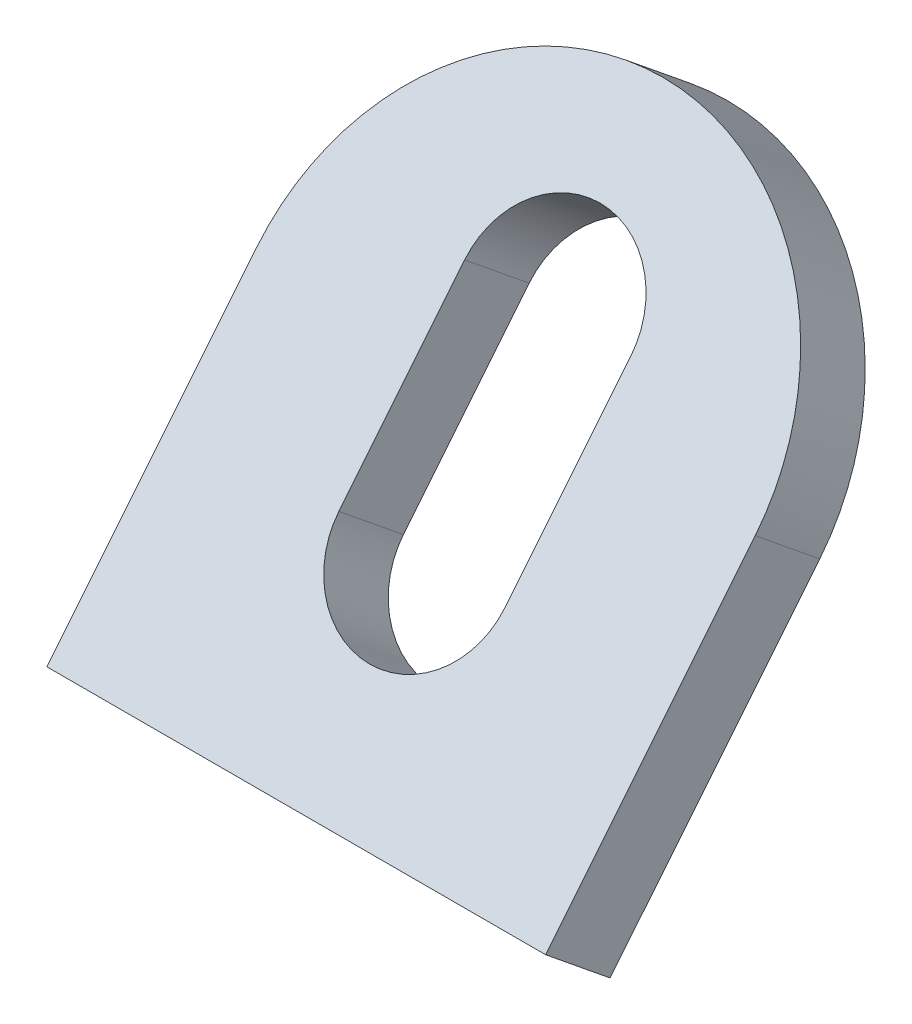
SolidWorks part; units mm, degrees
ref_plane "Front Plane" through (0, 0, 0) normal (0, 0, 1) x (1, 0, 0)
ref_plane "Top Plane" through (0, 0, 0) normal (0, 1, 0) x (1, 0, 0)
ref_plane "Right Plane" through (0, 0, 0) normal (1, 0, 0) x (0, 0, -1)
sketch "Sketch1" plane through (0, 861.7826, -474.0871) normal (0, -0.6305, -0.7762) x (1, 0, 0)
  line L0 (-319.2245, 531.8788) -> (319.2245, 531.8788) construction
  line L1 (-223.7213, 531.8788) -> (-204.6713, 531.8788)
  line L2 (-223.7213, 531.8788) -> (-223.7213, 519.1788)
  line L4 (-204.6713, 531.8788) -> (-204.6713, 519.1788)
  line L5 (-211.0213, 516.6388) -> (-211.0213, 524.2588)
  line L6 (-217.3713, 524.2588) -> (-217.3713, 516.6388)
  arc A0 (-223.7213, 519.1788) -> (-204.6713, 519.1788) centre (-214.1963, 519.1788) ccw
  arc A1 (-217.3713, 516.6388) -> (-211.0213, 516.6388) centre (-214.1963, 516.6388) ccw
  arc A2 (-211.0213, 524.2588) -> (-217.3713, 524.2588) centre (-214.1963, 524.2588) ccw
  point P16 (-214.1963, 531.8788)
  dimension "D3" = 6.35
  dimension "D4" = 9.525
  dimension "D1" = 19.05
  dimension "D2" = 12.7
  dimension "D5" = 7.62
  dimension "D6" = 7.62
  dimension "D7" = 101.6
extrude "Boss-Extrude1" add sketch "Sketch1" along normal blind 3.175
